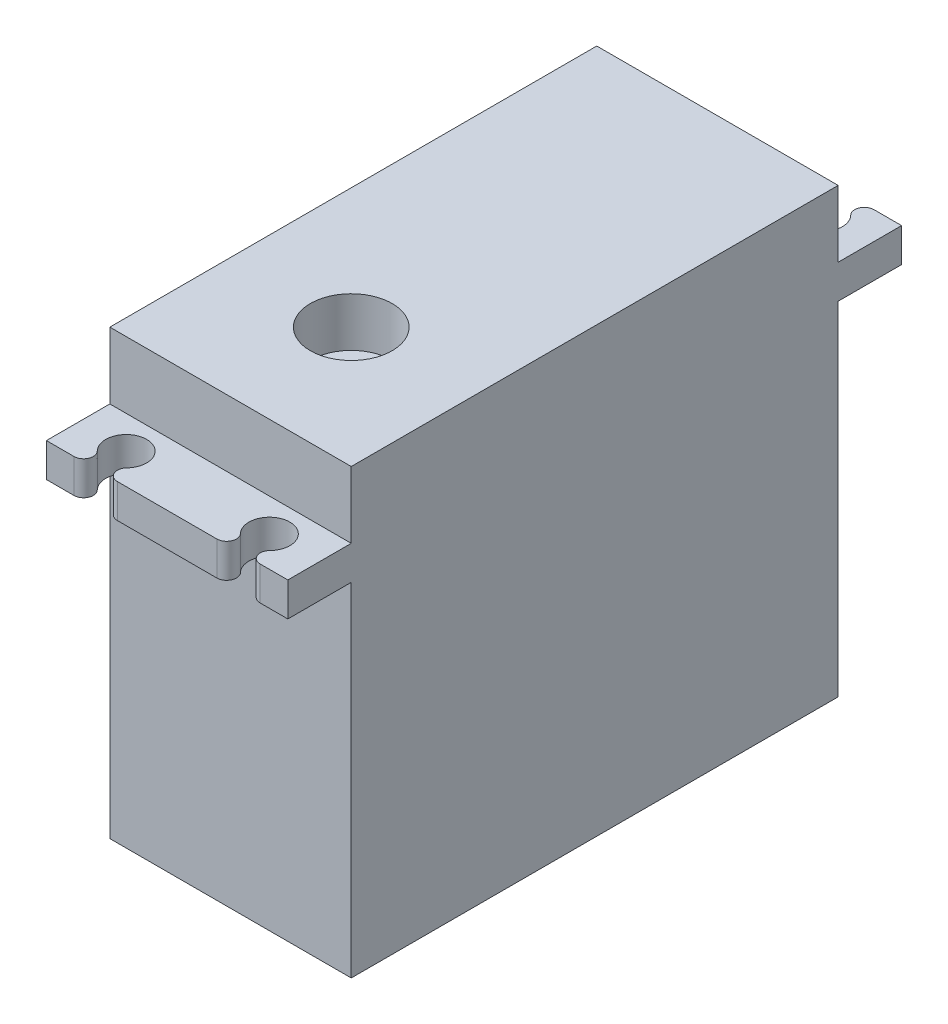
SolidWorks part; units mm, degrees
ref_plane "Front Plane" through (0, 0, 0) normal (0, 0, 1) x (1, 0, 0)
ref_plane "Top Plane" through (0, 0, 0) normal (0, 1, 0) x (1, 0, 0)
ref_plane "Right Plane" through (0, 0, 0) normal (1, 0, 0) x (0, 0, -1)
sketch "Sketch1" plane through (0, 0, 0) normal (0, 1, 0) x (1, 0, 0)
  line L1 (-14.75, -29.75) -> (14.75, -29.75)
  line L2 (-14.75, -29.75) -> (-14.75, 29.75)
  line L3 (-14.75, 29.75) -> (14.75, 29.75)
  line L4 (14.75, -29.75) -> (14.75, 29.75)
  line L5 (-14.75, -29.75) -> (14.75, 29.75) construction
  line L6 (-14.75, 29.75) -> (14.75, -29.75) construction
  point P0 (0, 0)
  dimension "D1" = 59.5
  dimension "D2" = 29.5
extrude "Boss-Extrude1" add sketch "Sketch1" along normal blind 54.13
sketch "Sketch2" plane through (0, 0, 29.75) normal (0, 0, 1) x (1, 0, 0)
  line L0 (-14.75, 54.13) -> (-14.75, 0) construction
  line L1 (-14.75, 41.87) -> (14.75, 41.87)
  line L2 (-14.75, 41.87) -> (-14.75, 46)
  line L3 (-14.75, 46) -> (14.75, 46)
  line L4 (14.75, 41.87) -> (14.75, 46)
  line L5 (14.75, 54.13) -> (14.75, 0) construction
  line L8 (-14.75, 0) -> (14.75, 0) construction
  dimension "D1" = 4.13
  dimension "D2" = 46
extrude "Boss-Extrude2" add sketch "Sketch2" along normal blind 7.75 contours L3 L4 L1 L2
sketch "Sketch3" plane through (0, 46, 0) normal (0, 1, 0) x (1, 0, 0)
  line L0 (-14.75, -37.5) -> (14.75, -37.5) construction
  line L1 (14.75, -37.5) -> (14.75, -29.75) construction
  line L2 (0, -29.75) -> (0, -37.5) construction
  line L3 (-14.75, -29.75) -> (14.75, -29.75) construction
  line L4 (6.0795, -37.5) -> (11.376, -37.5)
  line L5 (-6.0795, -37.5) -> (-11.376, -37.5)
  arc A0 (10.5356, -35.4998) -> (6.9434, -35.4781) centre (8.75, -33.75) ccw
  arc A1 (-10.5356, -35.4998) -> (-6.9434, -35.4781) centre (-8.75, -33.75) cw
  arc A2 (6.0795, -37.5) -> (6.9434, -35.4781) centre (6.0795, -36.3045) ccw
  arc A3 (10.5356, -35.4998) -> (11.376, -37.5) centre (11.376, -36.3233) ccw
  arc A4 (-10.5356, -35.4998) -> (-11.376, -37.5) centre (-11.376, -36.3233) cw
  arc A5 (-6.0795, -37.5) -> (-6.9434, -35.4781) centre (-6.0795, -36.3045) cw
  dimension "D1" = 5
  dimension "D2" = 3.75
  dimension "D3" = 6
extrude "Cut-Extrude1" cut sketch "Sketch3" against normal up to next
mirror "Mirror2" about plane through (0, 0, 0) normal (0, 0, 1) of "Cut-Extrude1", "Boss-Extrude2"
sketch "Sketch4" plane through (0, 54.13, 0) normal (0, 1, 0) x (1, 0, 0)
  line L0 (0, -29.75) -> (0, 29.75) construction
  line L1 (-14.75, -29.75) -> (14.75, -29.75) construction
  line L2 (14.75, 29.75) -> (-14.75, 29.75) construction
  circle A0 centre (0, -15) radius 5
  dimension "D2" = 10
  dimension "D1" = 14.75
extrude "Cut-Extrude2" cut sketch "Sketch4" against normal blind 6
